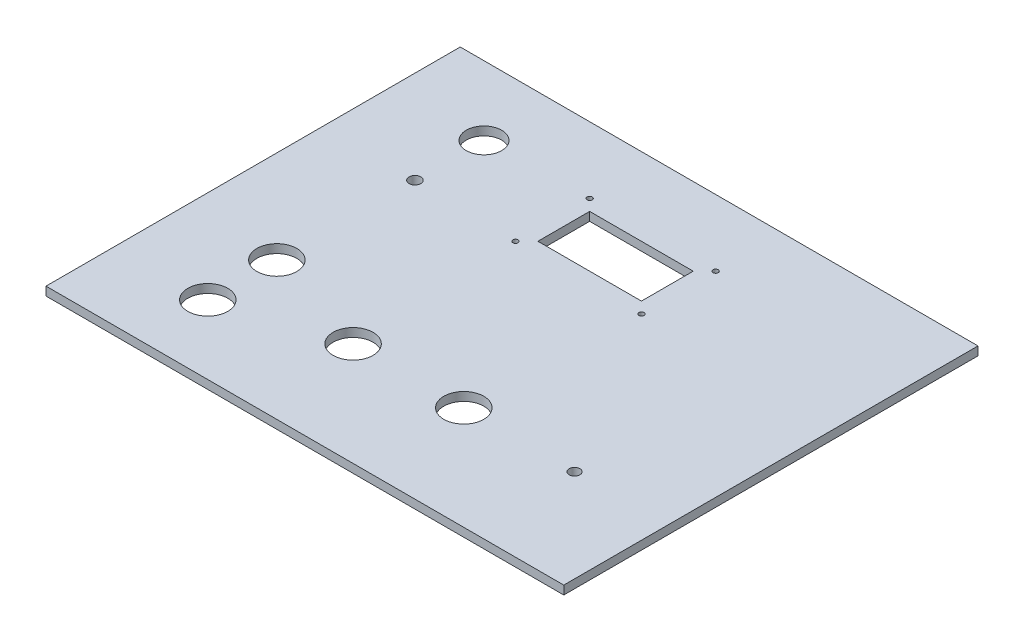
SolidWorks part; units mm, degrees
ref_plane "Front Plane" through (0, 0, 0) normal (0, 0, 1) x (1, 0, 0)
ref_plane "Top Plane" through (0, 0, 0) normal (0, 1, 0) x (1, 0, 0)
ref_plane "Right Plane" through (0, 0, 0) normal (1, 0, 0) x (0, 0, -1)
sketch "Sketch1" plane through (0, 0, 0) normal (0, 1, 0) x (1, 0, 0)
  line L1 (-150, -120) -> (150, -120)
  line L2 (-150, -120) -> (-150, 120)
  line L3 (-150, 120) -> (150, 120)
  line L4 (150, -120) -> (150, 120)
  line L5 (-150, -120) -> (150, 120) construction
  line L6 (-150, 120) -> (150, -120) construction
  point P0 (0, 0)
  dimension "D1" = 300
  dimension "D2" = 240
extrude "Boss-Extrude1" add sketch "Sketch1" along normal blind 5
sketch "Sketch2" plane through (0, 0, 0) normal (0, 1, 0) x (1, 0, 0)
  line L13 (-30, 45) -> (30, 45)
  line L17 (-30, 45) -> (-30, 75)
  line L22 (-30, 75) -> (30, 75)
  line L23 (30, 45) -> (30, 75)
  line L28 (-30, 45) -> (30, 75) construction
  line L29 (-30, 75) -> (30, 45) construction
  circle A0 centre (-96.25, 80) radius 10.25
  circle A2 centre (-96.25, -40) radius 11.58
  circle A3 centre (-96.25, -80) radius 11.58
  circle A6 centre (-96.25, 40) radius 3.4
  circle A7 centre (-32.08, -60) radius 11.58
  circle A8 centre (32.08, -60) radius 11.58
  circle A9 centre (96.25, -60) radius 3.1
  circle A10 centre (36.5, 38.5) radius 1.5
  circle A11 centre (36.5, 81.5) radius 1.5
  circle A12 centre (-36.5, 81.5) radius 1.5
  circle A13 centre (-36.5, 38.5) radius 1.5
  point P1 (0, 60)
  point P15 (0, 60)
  point P27 (0, 60)
  point P28 (0, 60)
  dimension "D5" = 43
  dimension "D6" = 73
  dimension "D1" = 60
  dimension "D2" = 30
extrude "Cut-Extrude4" cut sketch "Sketch2" along normal through all
